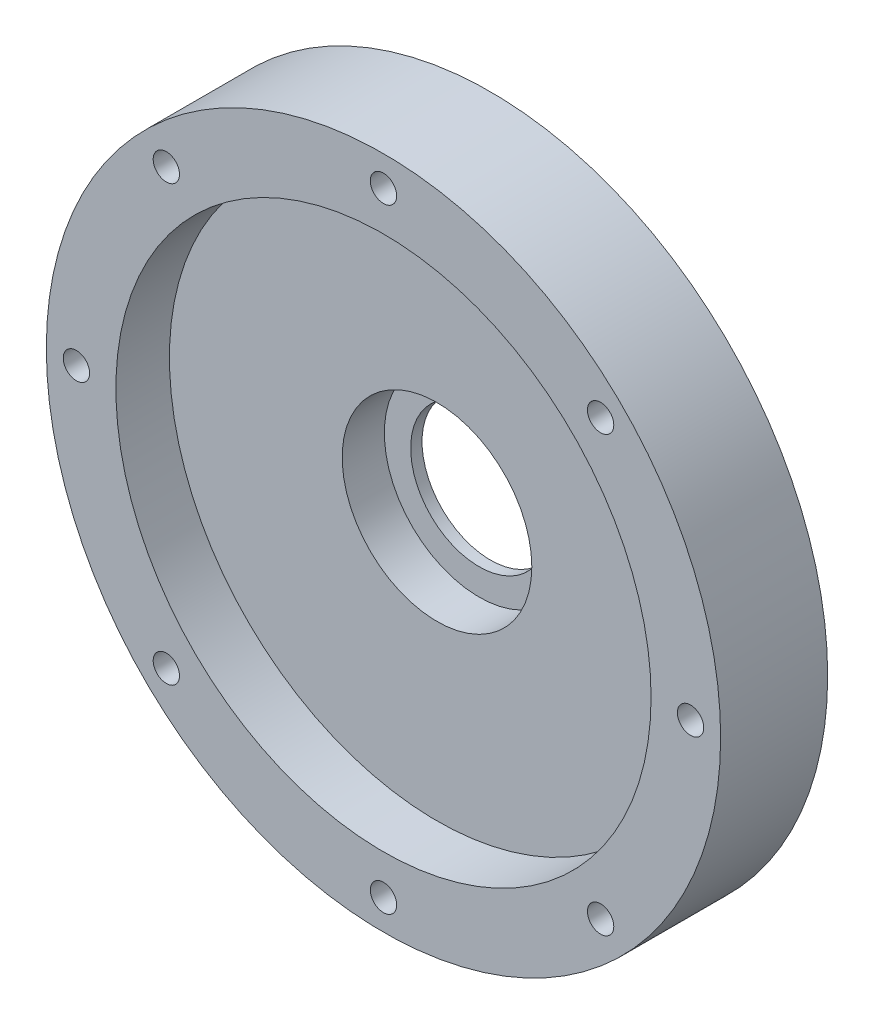
SolidWorks part; units mm, degrees
material "ABS PC"
ref_plane "Front Plane" through (0, 0, 0) normal (0, 0, 1) x (1, 0, 0)
ref_plane "Top Plane" through (0, 0, 0) normal (0, 1, 0) x (1, 0, 0)
ref_plane "Right Plane" through (0, 0, 0) normal (1, 0, 0) x (0, 0, -1)
sketch "Sketch1" plane through (0, 0, 0) normal (0, 0, 1) x (1, 0, 0)
  circle A0 centre (0, 0) radius 32.004
  dimension "D1" = 64.008
extrude "Boss-Extrude1" add sketch "Sketch1" along normal blind 10.16
sketch "Sketch2" plane through (0, 0, 10.16) normal (0, 0, 1) x (1, 0, 0)
  circle A0 centre (0, 0) radius 25.4
  dimension "D1" = 50.8
extrude "Cut-Extrude1" cut sketch "Sketch2" against normal blind 5.08
sketch "Sketch3" plane through (0, 0, 5.08) normal (0, 0, 1) x (1, 0, 0)
  circle A0 centre (0, 0) radius 9
  dimension "D1" = 18
extrude "Cut-Extrude2" cut sketch "Sketch3" against normal blind 4
sketch "Sketch4" plane through (0, 0, 1.08) normal (0, 0, 1) x (1, 0, 0)
  circle A0 centre (0, 0) radius 6.5
  dimension "D1" = 13
extrude "Cut-Extrude3" cut sketch "Sketch4" against normal through all
sketch "Sketch5" plane through (0, 0, 10.16) normal (0, 0, 1) x (1, 0, 0)
  line L0 (0, 0) -> (0, 32.004) construction
  line L2 (0, 0) -> (22.6302, 22.6302) construction
  line L3 (0, 0) -> (32.004, 0) construction
  line L4 (0, 0) -> (22.6302, -22.6302) construction
  line L5 (0, 0) -> (0, -32.004) construction
  line L6 (0, 0) -> (-22.6302, -22.6302) construction
  line L7 (0, 0) -> (-32.004, 0) construction
  line L8 (0, 0) -> (-22.6302, 22.6302) construction
  line L9 (0, 0) -> (0, 29.1465) construction
  circle A0 centre (0, 0) radius 32.004 construction
  circle A1 centre (0, 0) radius 25.4 construction
  point P6 (0, 29.1465)
  point P15 (20.6097, 20.6097)
  point P17 (29.1465, 0)
  point P19 (20.6097, -20.6097)
  point P21 (0, -29.1465)
  point P23 (-20.6097, -20.6097)
  point P25 (-29.1465, 0)
  point P27 (-20.6097, 20.6097)
  dimension "D1" = 29.1465
  dimension "D2" = 8
hole_wizard "M3x0.5 Tapped Hole1" positions "Sketch5" profile "Sketch6" tap size "M3x0.5" standard "ANSI Metric" end condition through all
sketch "Sketch6" plane through (-20.6097, 20.6097, 10.16) normal (1, 0, 0) x (0, -1, 0)
  line L0 (0, 0) -> (0, 10.16)
  line L1 (0, 10.16) -> (1.25, 10.16)
  line L2 (1.25, 10.16) -> (1.25, 0)
  line L5 (1.25, 0) -> (0, 0)
  line L11 (0, -6.35) -> (0, 107.95) construction
  dimension "Thru Tap Drill Dia." = 2.5
  dimension "Thru Tap Drill Depth" = 10.16
cosmetic thread "Hole Thread1" parameters "D2"=3
cosmetic thread "Hole Thread2" parameters "D2"=3
cosmetic thread "Hole Thread3" parameters "D2"=3
cosmetic thread "Hole Thread4" parameters "D2"=3
cosmetic thread "Hole Thread5" parameters "D2"=3
cosmetic thread "Hole Thread6" parameters "D2"=3
cosmetic thread "Hole Thread7" parameters "D2"=3
cosmetic thread "Hole Thread8" parameters "D2"=3
